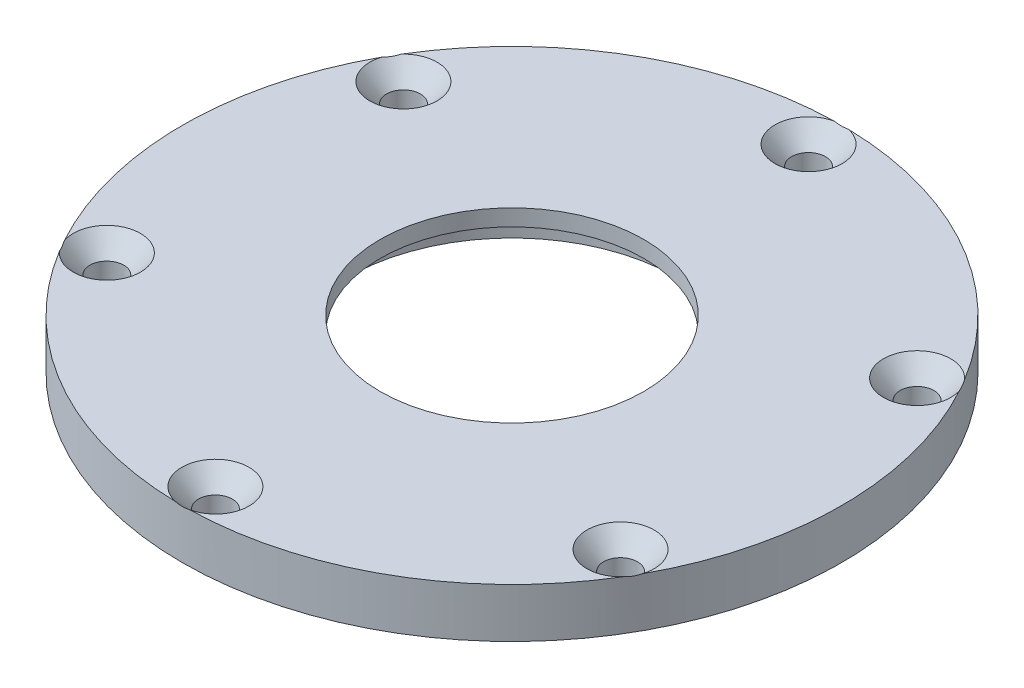
SolidWorks part; units mm, degrees
material "6061-T6 (SS)"
ref_plane "Front Plane" through (0, 0, 0) normal (0, 0, 1) x (1, 0, 0)
ref_plane "Top Plane" through (0, 0, 0) normal (0, 1, 0) x (1, 0, 0)
ref_plane "Right Plane" through (0, 0, 0) normal (1, 0, 0) x (0, 0, -1)
sketch "Sketch1" plane through (0, 0, 0) normal (0, 1, 0) x (1, 0, 0)
  circle A0 centre (0, 0) radius 31.75
  dimension "D1" = 63.5
extrude "Boss-Extrude1" add sketch "Sketch1" along normal blind 4.7625
hole_wizard "CSK for #4 Flat Head Socket Cap Screw1" positions "Sketch5" profile "Sketch4" countersink size "#4" standard "Ansi Inch" end condition through all
sketch "Sketch5" plane through (0, 4.7625, 0) normal (0, 1, 0) x (-1, 0, 0)
  point P0 (0, 28.575)
  point P24 (24.7467, 14.2875)
  point P25 (24.7467, -14.2875)
  point P26 (0, -28.575)
  point P27 (-24.7467, -14.2875)
  point P28 (-24.7467, 14.2875)
  dimension "D1" = 28.575
  dimension "D2" = 6
sketch "Sketch4" plane through (0, 4.7625, 28.575) normal (1, 0, 0) x (0, 0, 1)
  line L0 (0, 0) -> (0, 4.7625)
  line L1 (0, 4.7625) -> (1.6319, 4.7625)
  line L2 (1.6319, 4.7625) -> (1.6319, 1.8481)
  line L3 (1.6319, 1.8481) -> (3.2385, 0)
  line L5 (3.2385, 0) -> (0, 0)
  line L6 (-1.6319, 1.8481) -> (-3.2385, 0) construction
  line L11 (0, -6.35) -> (0, 107.95) construction
  dimension "Thru Hole Dia." = 3.2639
  dimension "Thru Hole Depth" = 4.7625
  dimension "Near C'Sink Dia." = 6.477
  dimension "Near C'Sink Angle" = 82
sketch "Sketch6" plane through (0, 0, 0) normal (0, -1, 0) x (1, 0, 0)
  circle A0 centre (0, 0) radius 15.875
  dimension "D1" = 31.75
extrude "Cut-Extrude1" cut sketch "Sketch6" against normal blind 3.175
sketch "Sketch7" plane through (0, 3.175, 0) normal (0, -1, 0) x (1, 0, 0)
  circle A0 centre (0, 0) radius 12.7
  dimension "D1" = 25.4
extrude "Cut-Extrude2" cut sketch "Sketch7" against normal blind 3.175
sketch "Sketch8" plane through (0, 0, 0) normal (0, -1, 0) x (1, 0, 0)
  arc A0 (-3.167, 28.3494) -> (3.167, 28.3494) centre (0, 28.575) ccw
  circle A1 centre (0, 0) radius 31.75 construction
  arc A2 (22.9678, 16.9174) -> (26.1348, 11.432) centre (24.7467, 14.2875) ccw
  arc A3 (24.649, 17.461) -> (27.4462, 12.6162) centre (24.7467, 14.2875) ccw
  arc A4 (26.1348, -11.432) -> (22.9678, -16.9174) centre (24.7467, -14.2875) ccw
  arc A5 (3.167, -28.3494) -> (-3.167, -28.3494) centre (0, -28.575) ccw
  circle A6 centre (0, 0) radius 17.4625
  arc A7 (-4.9984, 29.7905) -> (-23.3002, 19.224) centre (0, 0) ccw
  arc A8 (-22.9678, -16.9174) -> (-26.1348, -11.432) centre (-24.7467, -14.2875) ccw
  arc A9 (-26.1348, 11.432) -> (-22.9678, 16.9174) centre (-24.7467, 14.2875) ccw
  circle A10 centre (24.7467, -14.2875) radius 3.175 [skipped]
  circle A11 centre (0, -28.575) radius 3.175 [skipped]
  circle A12 centre (-24.7467, -14.2875) radius 3.175 [skipped]
  circle A13 centre (-24.7467, 14.2875) radius 3.175 [skipped]
  circle A14 centre (0, 28.575) radius 1.632 construction
  arc A15 (23.3002, 19.224) -> (4.9984, 29.7905) centre (0, 0) ccw
  arc A16 (-28.2985, 10.5665) -> (-28.2985, -10.5665) centre (0, 0) ccw
  arc A17 (-23.3002, -19.224) -> (-4.9984, -29.7905) centre (0, 0) ccw
  arc A18 (4.9984, -29.7905) -> (23.3002, -19.224) centre (0, 0) ccw
  arc A19 (28.2985, -10.5665) -> (28.2985, 10.5665) centre (0, 0) ccw
  arc A20 (-3.167, -28.3494) -> (-4.9984, -29.7905) centre (-4.7378, -28.2374) cw
  arc A21 (-26.1348, -11.432) -> (-28.2985, -10.5665) centre (-26.8232, -10.0157) cw
  arc A22 (-22.9678, -16.9174) -> (-23.3002, -19.224) centre (-22.0855, -18.2218) ccw
  arc A23 (22.9678, -16.9174) -> (23.3002, -19.224) centre (22.0855, -18.2218) cw
  arc A24 (26.1348, -11.432) -> (28.2985, -10.5665) centre (26.8232, -10.0157) ccw
  arc A25 (-26.1348, 11.432) -> (-28.2985, 10.5665) centre (-26.8232, 10.0157) ccw
  arc A26 (-22.9678, 16.9174) -> (-23.3002, 19.224) centre (-22.0855, 18.2218) cw
  arc A27 (3.167, 28.3494) -> (4.9984, 29.7905) centre (4.7378, 28.2374) cw
  arc A28 (-3.167, 28.3494) -> (-4.9984, 29.7905) centre (-4.7378, 28.2374) ccw
  arc A29 (3.167, -28.3494) -> (4.9984, -29.7905) centre (4.7378, -28.2374) ccw
  arc A30 (22.9678, 16.9174) -> (23.3002, 19.224) centre (22.0855, 18.2218) ccw
  arc A31 (26.1348, 11.432) -> (28.2985, 10.5665) centre (26.8232, 10.0157) cw
  point P43 (-2.7972, -30.0772)
  point P46 (-27.4462, -12.6162)
  point P49 (-24.649, -17.461)
  point P52 (24.649, -17.461)
  point P55 (27.4462, -12.6162)
  point P58 (-27.4462, 12.6162)
  point P67 (2.7972, -30.0772)
  dimension "D1" = 34.925
  dimension "D2" = 1.5748
  dimension "D4" = 1.5748
  dimension "D5" = 1.5748
  dimension "D3" = 6
extrude "Cut-Extrude3" cut sketch "Sketch8" against normal blind 3.175 contours A31 A2 A30 A15 A27 A0 A28 A7 A26 A9 A25 A16 A21 A8 A22 A17 A20 A5 A29 A18 A23 A4 A24 A19 A6
